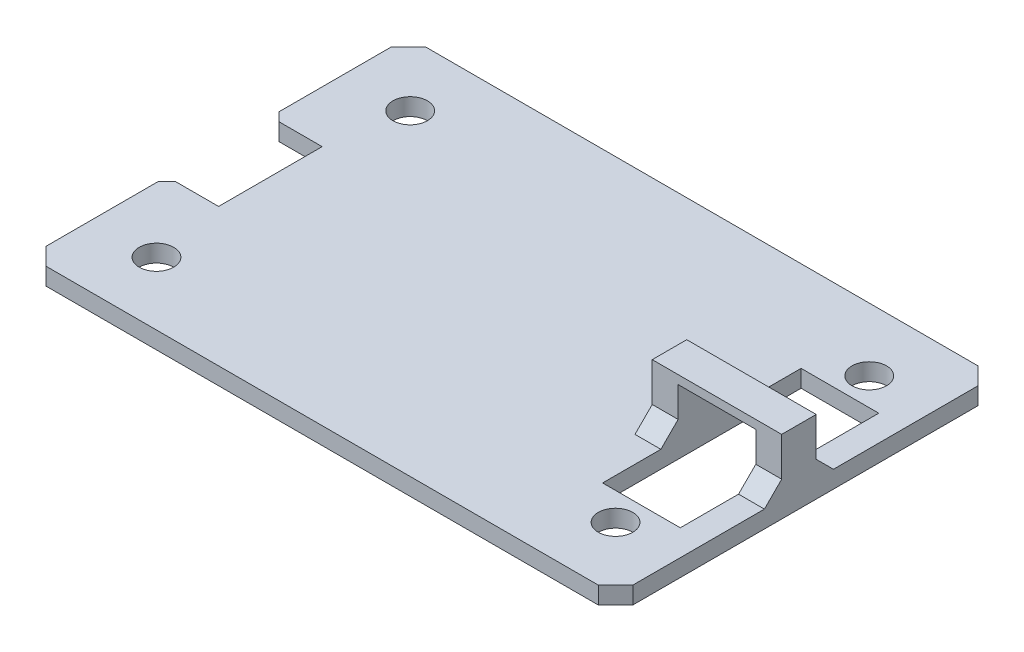
SolidWorks part; units mm, degrees
ref_plane "Front Plane" through (0, 0, 0) normal (0, 0, 1) x (1, 0, 0)
ref_plane "Top Plane" through (0, 0, 0) normal (0, 1, 0) x (1, 0, 0)
ref_plane "Right Plane" through (0, 0, 0) normal (1, 0, 0) x (0, 0, -1)
sketch "Sketch1" plane through (0, 0, 0) normal (0, 1, 0) x (1, 0, 0)
  line L1 (-29.6081, 14.5531) -> (38.3919, 14.5531)
  line L2 (-29.6081, 14.5531) -> (-29.6081, -29.4469)
  line L3 (-29.6081, -29.4469) -> (38.3919, -29.4469)
  line L4 (38.3919, 14.5531) -> (38.3919, -29.4469)
  dimension "D1" = 68
  dimension "D2" = 44
extrude "Boss-Extrude1" add sketch "Sketch1" along normal blind 2
sketch "Sketch2" plane through (0, 2, 0) normal (0, 1, 0) x (1, 0, 0)
  line L0 (38.3919, 14.5531) -> (-29.6081, 14.5531) construction
  line L1 (-29.6081, 14.5531) -> (-29.6081, -29.4469) construction
  line L2 (38.3919, -29.4469) -> (38.3919, 14.5531) construction
  line L3 (-29.6081, -29.4469) -> (38.3919, -29.4469) construction
  circle A0 centre (-22.1081, 7.2531) radius 2
  circle A1 centre (31.0919, 7.2531) radius 2
  circle A2 centre (31.0919, -22.1469) radius 2
  circle A3 centre (-22.1081, -22.1469) radius 2
  dimension "D1" = 4
  dimension "D2" = 4
  dimension "D3" = 4
  dimension "D4" = 4
  dimension "D5" = 7.3
  dimension "D6" = 7.5
  dimension "D7" = 7.3
  dimension "D8" = 7.3
  dimension "D9" = 7.3
  dimension "D10" = 7.3
  dimension "D11" = 7.3
  dimension "D12" = 7.5
extrude "Cut-Extrude1" cut sketch "Sketch2" against normal blind 2
sketch "Sketch3" plane through (0, 2, 0) normal (0, 1, 0) x (1, 0, 0)
  line L0 (38.3919, -29.4469) -> (38.3919, 14.5531) construction
  line L1 (38.3919, 4.0531) -> (26.3919, 4.0531)
  line L2 (38.3919, 4.0531) -> (38.3919, -18.9469)
  line L3 (38.3919, -18.9469) -> (26.3919, -18.9469)
  line L4 (26.3919, 4.0531) -> (26.3919, -18.9469)
  line L5 (38.3919, 14.5531) -> (-29.6081, 14.5531) construction
  dimension "D1" = 12
  dimension "D2" = 23
  dimension "D3" = 10.5
extrude "Cut-Extrude2" cut sketch "Sketch3" against normal blind 2
sketch "Sketch4" plane through (0, 2, 0) normal (0, 1, 0) x (1, 0, 0)
  line L0 (26.3919, -18.9469) -> (38.3919, -18.9469) construction
  line L1 (38.3919, 4.0531) -> (35.3919, 4.0531)
  line L2 (38.3919, 4.0531) -> (38.3919, -18.9469)
  line L3 (38.3919, -18.9469) -> (35.3919, -18.9469)
  line L4 (35.3919, 4.0531) -> (35.3919, -18.9469)
  dimension "D1" = 3
extrude "Boss-Extrude2" add sketch "Sketch4" against normal blind 2
sketch "Sketch5" plane through (0, 2, 0) normal (0, 1, 0) x (1, 0, 0)
  line L0 (38.3919, -29.4469) -> (38.3919, 14.5531) construction
  line L1 (35.3919, 4.0531) -> (38.3919, 4.0531)
  line L2 (35.3919, 4.0531) -> (35.3919, -17.4469)
  line L3 (35.3919, -17.4469) -> (38.3919, -17.4469)
  line L4 (38.3919, 4.0531) -> (38.3919, -17.4469)
  line L6 (26.3919, -18.9469) -> (23.3919, -18.9469)
  line L7 (26.3919, -18.9469) -> (26.3919, 2.5531)
  line L8 (26.3919, 2.5531) -> (23.3919, 2.5531)
  line L9 (23.3919, -18.9469) -> (23.3919, 2.5531)
  dimension "D1" = 3
extrude "Boss-Extrude3" add sketch "Sketch5" along normal blind 6.5
sketch "Sketch6" plane through (26.3919, 0, 0) normal (1, 0, 0) x (0, 0, -1)
  line L0 (-18.9469, 8.5) -> (2.5531, 8.5) construction
  line L1 (-10.1969, 8.5) -> (-6.1969, 8.5)
  line L2 (-10.1969, 8.5) -> (-10.1969, 6.5)
  line L3 (-10.1969, 6.5) -> (-6.1969, 6.5)
  line L4 (-6.1969, 8.5) -> (-6.1969, 6.5)
  point P6 (-8.1969, 8.5)
  dimension "D1" = 2
  dimension "D2" = 2
  dimension "D3" = 2
extrude "Boss-Extrude4" add sketch "Sketch6" along normal blind 10
sketch "Sketch7" plane through (26.3919, 0, 0) normal (1, 0, 0) x (0, 0, -1)
  line L1 (-10.1969, 8.5) -> (-18.9469, 8.5)
  line L2 (-10.1969, 8.5) -> (-10.1969, 2)
  line L3 (-10.1969, 2) -> (-18.9469, 2)
  line L4 (-18.9469, 8.5) -> (-18.9469, 2)
  line L5 (-6.1969, 8.5) -> (4.0531, 8.5)
  line L6 (-6.1969, 8.5) -> (-6.1969, 2)
  line L7 (-6.1969, 2) -> (4.0531, 2)
  line L8 (4.0531, 8.5) -> (4.0531, 2)
extrude "Cut-Extrude3" cut sketch "Sketch7" against normal blind 20 and the other way blind 20
chamfer "Chamfer1" distance 2 angle 45 4 edges at (24.8919, 2, 10.1969) (36.8919, 2, 10.1969) (36.8919, 2, 6.1969) (24.8919, 2, 6.1969)
sketch "Sketch8" plane through (0, 2, 0) normal (0, 1, 0) x (1, 0, 0)
  line L0 (-29.6081, 14.5531) -> (-29.6081, -29.4469) construction
  line L1 (-29.6081, -13.4469) -> (-23.6081, -13.4469)
  line L2 (-29.6081, -13.4469) -> (-29.6081, -1.4469)
  line L3 (-29.6081, -1.4469) -> (-23.6081, -1.4469)
  line L4 (-23.6081, -13.4469) -> (-23.6081, -1.4469)
  line L5 (38.3919, 14.5531) -> (-29.6081, 14.5531) construction
  line L6 (-29.6081, -29.4469) -> (38.3919, -29.4469) construction
  dimension "D1" = 16
  dimension "D2" = 16
  dimension "D3" = 6
extrude "Cut-Extrude4" cut sketch "Sketch8" against normal blind 20
chamfer "Chamfer2" distance 1 angle 45 2 edges at (-29.6081, 1, 1.4469) (-29.6081, 1, 13.4469)
chamfer "Chamfer3" distance 1 angle 45 1 edges at (30.8919, 6.5, 10.1969)
chamfer "Chamfer4" distance 2 angle 45 4 edges at (38.3919, 1, 29.4469) (38.3919, 1, -14.5531) (-29.6081, 1, -14.5531) (-29.6081, 1, 29.4469)
